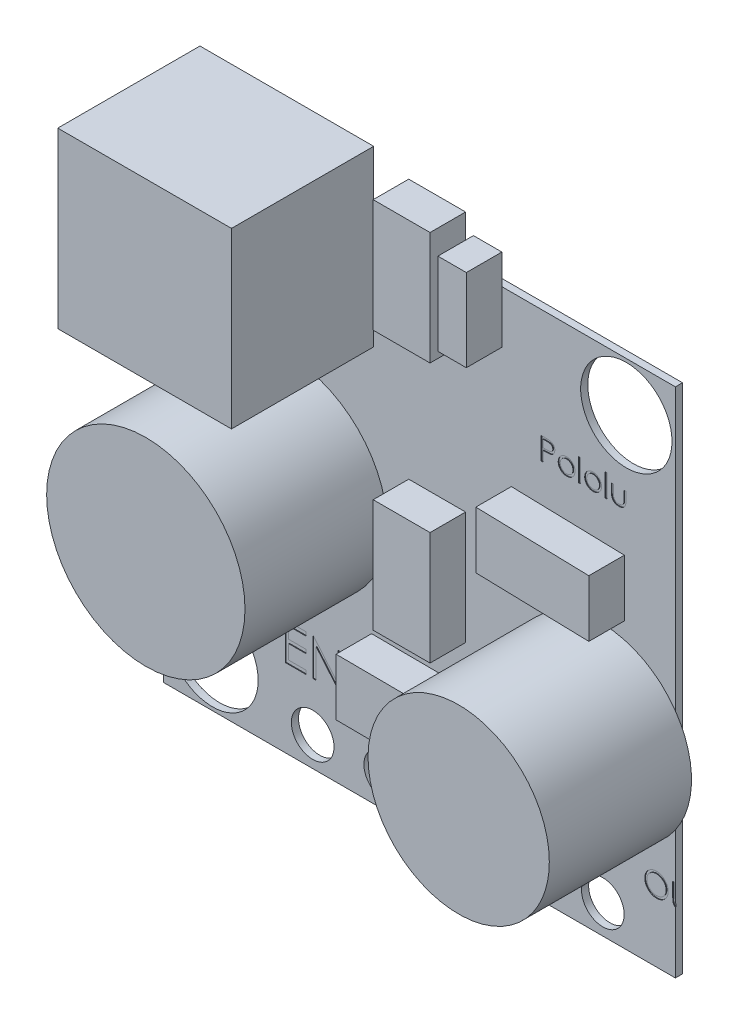
SolidWorks part; units mm, degrees
ref_plane "Front Plane" through (0, 0, 0) normal (0, 0, 1) x (1, 0, 0)
ref_plane "Top Plane" through (0, 0, 0) normal (0, 1, 0) x (1, 0, 0)
ref_plane "Right Plane" through (0, 0, 0) normal (1, 0, 0) x (0, 0, -1)
sketch "Sketch1" plane through (0, 0, 0) normal (0, 0, 1) x (1, 0, 0)
  line L0 (0.669, -0.5811) -> (0.669, 1.1715) construction
  line L1 (-1.0836, -0.5811) -> (17.2082, -0.5811)
  line L2 (-1.0836, -0.5811) -> (-1.0836, 17.7107)
  line L3 (-1.0836, 17.7107) -> (17.2082, 17.7107)
  line L4 (17.2082, -0.5811) -> (17.2082, 17.7107)
  line L5 (0.669, 1.1715) -> (-1.0836, 1.1715) construction
  line L6 (15.4556, 17.7107) -> (15.4556, 15.9581) construction
  line L7 (15.4556, 15.9581) -> (17.2082, 15.9581) construction
  line L8 (-1.0836, 0.4655) -> (4.2504, 0.4655) construction
  line L9 (4.2504, 0.4655) -> (6.8419, 0.4655) construction
  line L10 (6.8419, 0.4655) -> (9.4335, 0.4655) construction
  line L11 (9.4335, 0.4655) -> (12.0251, 0.4655) construction
  line L12 (12.0251, 0.4655) -> (14.6166, 0.4655) construction
  line L13 (14.6166, 0.4655) -> (17.2082, 0.4655) construction
  circle A0 centre (0.669, 1.1715) radius 1.632
  circle A1 centre (15.4556, 15.9581) radius 1.632
  circle A2 centre (4.2504, 0.4655) radius 0.762
  circle A3 centre (6.8419, 0.4655) radius 0.762
  circle A4 centre (9.4335, 0.4655) radius 0.762
  circle A5 centre (12.0251, 0.4655) radius 0.762
  circle A6 centre (14.6166, 0.4655) radius 0.762
  dimension "D1" = 3.2639
  dimension "D2" = 20.9115
extrude "Boss-Extrude2" add sketch "Sketch1" along normal blind 0.254
sketch "Sketch2" plane through (0, 0, 0.254) normal (0, 0, 1) x (1, 0, 0)
  line L0 (17.2082, 17.7107) -> (-1.0836, 17.7107) construction
  line L1 (0.2217, 19.7636) -> (6.428, 19.7636)
  line L2 (0.2217, 19.7636) -> (0.2217, 13.5573)
  line L3 (0.2217, 13.5573) -> (6.428, 13.5573)
  line L4 (6.428, 19.7636) -> (6.428, 13.5573)
  circle A0 centre (3.3674, 8.2222) radius 3.5433
  circle A1 centre (14.5452, 5.8421) radius 3.2385
extrude "Boss-Extrude3" add sketch "Sketch2" along normal blind 5.08
sketch "Sketch3" plane through (0, 0, 0.254) normal (0, 0, 1) x (1, 0, 0)
  line L1 (6.3544, 4.6463) -> (10.3929, 4.6203)
  line L2 (6.3544, 4.6463) -> (6.3545, 2.6143)
  line L3 (6.3545, 2.6143) -> (10.393, 2.5883)
  line L4 (10.3929, 4.6203) -> (10.393, 2.5883)
  line L5 (7.6807, 10.0893) -> (9.7127, 10.0893)
  line L6 (7.6807, 10.0893) -> (7.6807, 6.0507)
  line L7 (7.6807, 6.0507) -> (9.7127, 6.0507)
  line L8 (9.7127, 10.0893) -> (9.7127, 6.0507)
  line L9 (7.6807, 19.3736) -> (9.7127, 19.3736)
  line L10 (7.6807, 19.3736) -> (7.6807, 15.335)
  line L11 (7.6807, 15.335) -> (9.7127, 15.335)
  line L12 (9.7127, 19.3736) -> (9.7127, 15.335)
  line L13 (11.3476, 11.6941) -> (15.3849, 11.59)
  line L14 (11.3476, 11.6941) -> (11.3498, 9.6621)
  line L15 (11.3498, 9.6621) -> (15.3871, 9.558)
  line L16 (15.3849, 11.59) -> (15.3871, 9.558)
  line L17 (9.9933, 18.7829) -> (11.0093, 18.7829)
  line L18 (9.9933, 18.7829) -> (9.9933, 15.8365)
  line L19 (9.9933, 15.8365) -> (11.0093, 15.8365)
  line L20 (11.0093, 18.7829) -> (11.0093, 15.8365)
extrude "Boss-Extrude4" add sketch "Sketch3" along normal blind 1.27
sketch "Sketch4" plane through (0, 0, 0.254) normal (0, 0, 1) x (1, 0, 0)
  line L0 (12.3098, 13.0148) -> (16.1369, 13.0148) construction
  line L1 (3.1036, 2.2107) -> (4.2739, 2.2107) construction
  line L2 (7.0305, 1.6185) -> (8.0968, 1.6185) construction
  line L3 (10.3594, 1.6296) -> (12.3098, 1.6296) construction
  line L4 (16.0548, 1.5708) -> (18.4734, 1.5708) construction
  line L5 (17.2082, 17.7107) -> (11.0093, 17.7107) construction
  text T0 "Pololu" font "Century Gothic" height in points 3
  text T1 "EN" font "Century Gothic" height in points 5
  text T2 "VIN" font "Century Gothic" height in points 3
  text T3 "GND" font "Century Gothic" height in points 3
  text T4 "OUT" font "Century Gothic" height in points 3
extrude "Cut-Extrude1" cut sketch "Sketch4" against normal blind 0.0254
